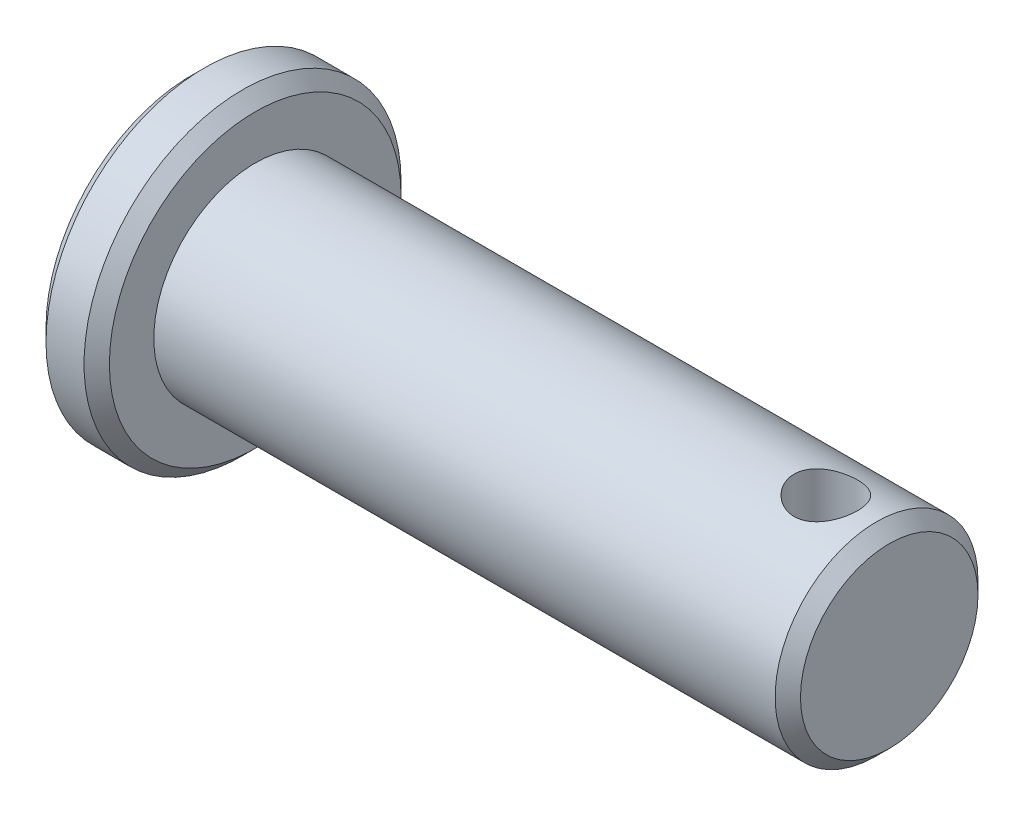
SolidWorks part; units mm, degrees
material "45"
ref_plane "前视基准面" through (0, 0, 0) normal (0, 0, 1) x (1, 0, 0)
ref_plane "上视基准面" through (0, 0, 0) normal (0, 1, 0) x (1, 0, 0)
ref_plane "右视基准面" through (0, 0, 0) normal (1, 0, 0) x (0, 0, -1)
sketch "草图1" plane through (0, 0, 0) normal (0, 0, 1) x (1, 0, 0)
  line L0 (0, 0) -> (-164.9766, 0) construction
  line L1 (-55, 0) -> (-55, 12.5)
  line L2 (-55, 12.5) -> (-50, 12.5)
  line L3 (-50, 12.5) -> (-50, 8)
  line L4 (-50, 8) -> (0, 8)
  line L5 (0, 8) -> (0, 0)
  line L6 (-55, 0) -> (0, 0)
  dimension "D1" = 50
  dimension "D2" = 25
  dimension "D3" = 5
  dimension "D4" = 16
revolve "旋转1" add sketch "草图1" angle 360 about L0
chamfer "倒角1" distance 1 angle 45 2 edges at (-50, 0, -12.5) (-55, 0, -12.5)
chamfer "倒角2" distance 1 angle 45 1 edges at (0, 0, -8)
sketch "草图2" plane through (0, 0, 0) normal (0, 1, 0) x (1, 0, 0)
  line L0 (0, 0) -> (-133.2201, 0) construction
  line L2 (0, -7) -> (0, 7) construction
  circle A0 centre (-5, 0) radius 2.5
  dimension "D1" = 5
  dimension "D2" = 5
extrude "切除-拉伸1" cut sketch "草图2" against normal mid plane 80
